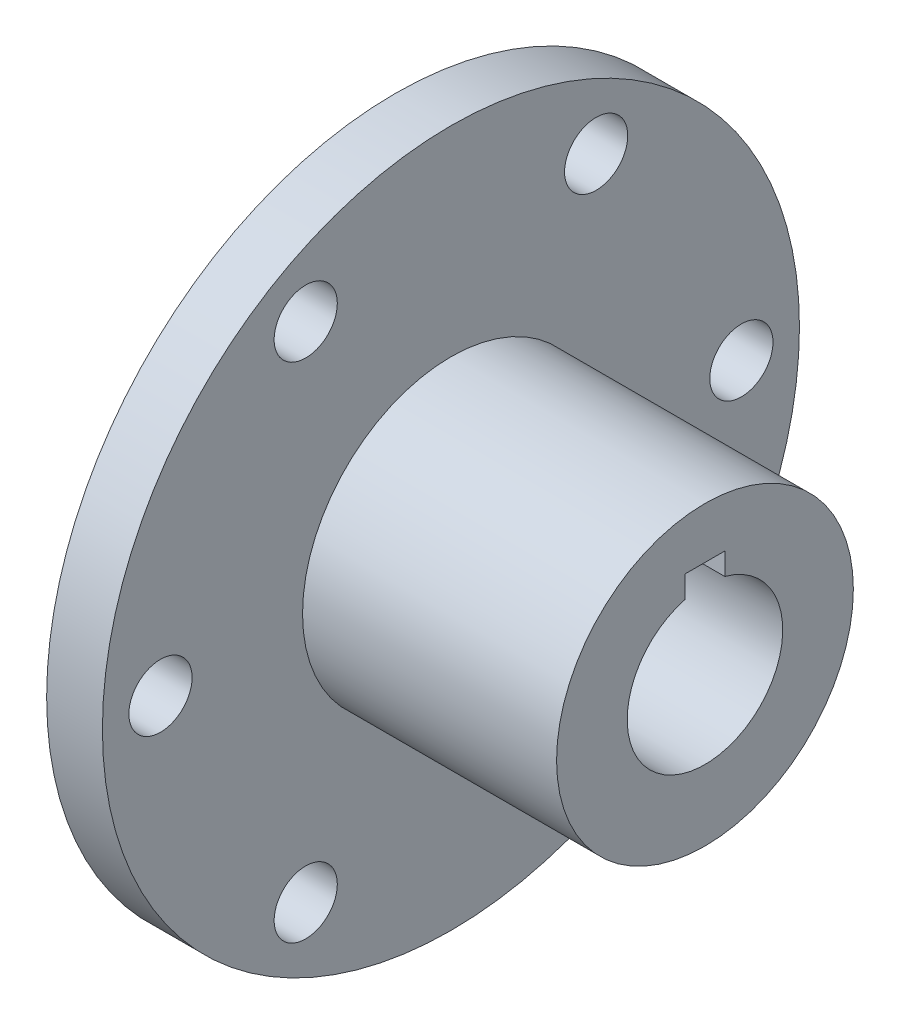
SolidWorks part; units mm, degrees
ref_plane "Front Plane" through (0, 0, 0) normal (0, 0, 1) x (1, 0, 0)
ref_plane "Top Plane" through (0, 0, 0) normal (0, 1, 0) x (1, 0, 0)
ref_plane "Right Plane" through (0, 0, 0) normal (1, 0, 0) x (0, 0, -1)
sketch "Sketch1" plane through (0, 0, 0) normal (0, 0, 1) x (1, 0, 0)
  line L0 (-17.6071, 28.575) -> (-17.6071, 0)
  line L1 (-17.6071, 0) -> (-13.0351, 0)
  line L2 (-13.0351, 0) -> (-13.0351, 28.575)
  line L3 (-13.0351, 28.575) -> (-17.6071, 28.575)
  line L4 (-17.6071, 0) -> (-13.0351, 0) construction
revolve "Revolve1" add sketch "Sketch1" angle 360 about L4
sketch "Sketch2" plane through (-13.0351, 0, 0) normal (1, 0, 0) x (0, 0, -1)
  circle A0 centre (0, 0) radius 12.1666
extrude "Boss-Extrude1" add sketch "Sketch2" along normal blind 20.828
sketch "Sketch3" plane through (-17.6071, 0, 0) normal (-1, 0, 0) x (0, 0, 1)
  line L0 (1.6256, 6.1647) -> (1.6256, 7.9756)
  line L1 (1.6256, 7.9756) -> (-1.6256, 7.9756)
  line L2 (-1.6256, 7.9756) -> (-1.6256, 6.1647)
  arc A0 (-1.6256, 6.1647) -> (1.6256, 6.1647) centre (0, 0) cw
extrude "Cut-Extrude1" cut sketch "Sketch3" against normal through all
ref_plane "Plane1" through (0, 0, 0) normal (0, 0, -1) x (-1, 0, 0)
sketch "Sketch4" plane through (0, 0, 0) normal (0, 0, -1) x (-1, 0, 0)
  line L0 (-7.7929, 6.3754) -> (-7.7929, 0)
  line L1 (-7.7929, 0) -> (17.6071, 0)
  line L2 (17.6071, 0) -> (17.6071, 6.3754)
  line L3 (17.6071, 6.3754) -> (-7.7929, 6.3754)
  line L4 (-7.7929, 0) -> (17.6071, 0) construction
revolve "Cut-Revolve1" cut sketch "Sketch4" angle 360 about L4
hole_wizard "Hole1" positions "Sketch6" profile "Sketch5" legacy
sketch "Sketch6" plane through (-17.6071, 0, 0) normal (-1, 0, 0) x (0, 0, 1)
  point P0 (23.8125, 0)
  point P1 (11.9062, 20.6222)
  point P2 (-11.9062, 20.6222)
  point P3 (-23.8125, 0)
  point P4 (-11.9062, -20.6222)
  point P5 (11.9062, -20.6222)
sketch "Sketch5" plane through (-17.6071, 0, 23.8125) normal (0, 1, 0) x (0, 0, 1)
  line L0 (0, 0) -> (0, 25.4)
  line L1 (0, 25.4) -> (2.5908, 25.4)
  line L2 (2.5908, 25.4) -> (2.5908, 0)
  line L3 (2.5908, 0) -> (0, 0)
  line L4 (0, 110) -> (0, -10) construction
  dimension "Diameter" = 5.1816
  dimension "Depth" = 25.4
